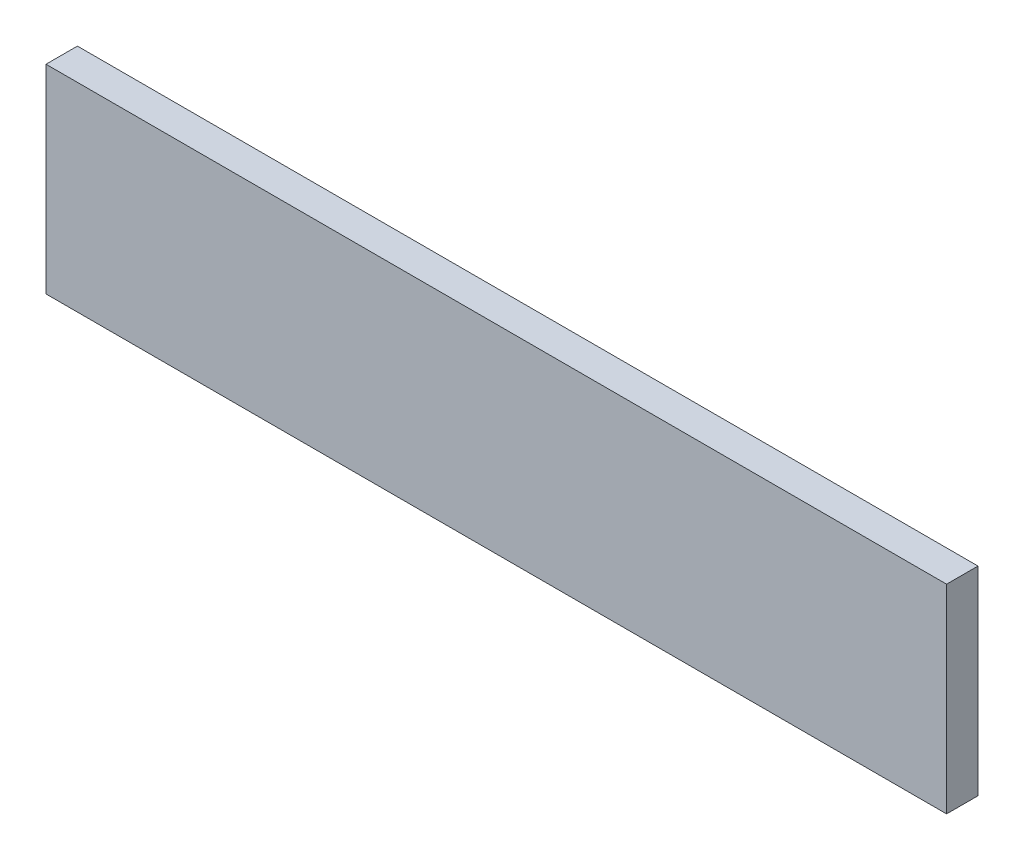
SolidWorks part; units mm, degrees
ref_plane "Plan de face" through (0, 0, 0) normal (0, 0, 1) x (1, 0, 0)
ref_plane "Plan de dessus" through (0, 0, 0) normal (0, 1, 0) x (1, 0, 0)
ref_plane "Plan de droite" through (0, 0, 0) normal (1, 0, 0) x (0, 0, -1)
sketch "Esquisse2" plane through (0, 0, 0) normal (0, 0, 1) x (1, 0, 0)
  line L1 (-215, -47.5) -> (215, -47.5)
  line L2 (-215, -47.5) -> (-215, 47.5)
  line L3 (-215, 47.5) -> (215, 47.5)
  line L4 (215, -47.5) -> (215, 47.5)
  line L5 (-215, -47.5) -> (215, 47.5) construction
  line L6 (-215, 47.5) -> (215, -47.5) construction
  point P0 (0, 0)
  dimension "D1" = 430
  dimension "D2" = 95
extrude "Boss.-Extru.1" add sketch "Esquisse2" along normal blind 15
